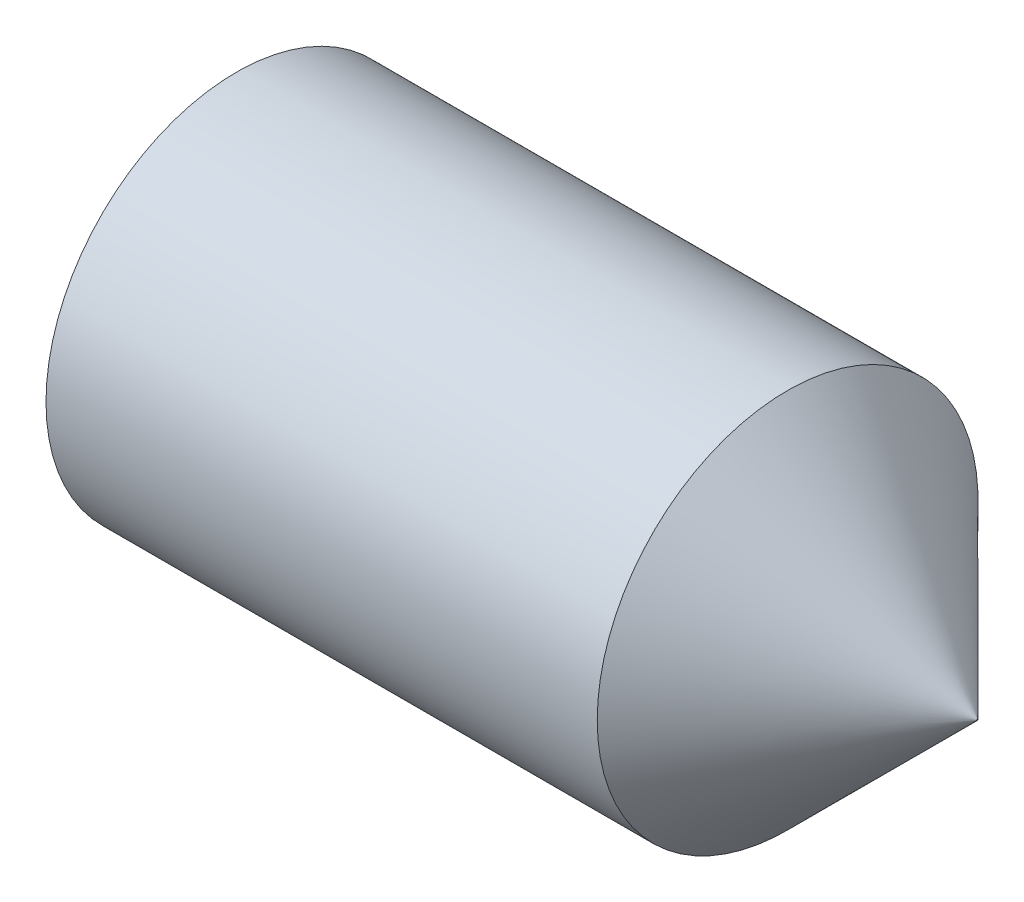
SolidWorks part; units mm, degrees
revolve "BaseBody" add sketch "BodySke" angle 360 about L5
sketch "BodySke" plane through (0, 0, 0) normal (0, 0, 1) x (1, 0, 0)
  line L0 (0, 0) -> (0, 1.2195)
  line L1 (0, 1.2195) -> (0.1619, 1.5)
  line L2 (0.1619, 1.5) -> (4.505, 1.5)
  line L3 (6, 0) -> (6, 0.005)
  line L4 (6, 0) -> (0, 0)
  line L5 (-12.7, 0) -> (88.9, 0) construction
  line L6 (6, 0.005) -> (4.505, 1.5)
  line L7 (0.5, 15.875) -> (0.5, -3.175) construction
  line L8 (0, -1.2195) -> (0.1619, -1.5) construction
  line L9 (6, -0.005) -> (4.505, -1.5) construction
  dimension "Diameter" = 3
  dimension "Drive_ch_ang" = 60
  dimension "Minor_dia" = 2.439
  dimension "Advance" = 0.5
  dimension "Length" = 6
  dimension "Tip_dia" = 0.01
  dimension "Cone_ang" = 90
cosmetic thread "ThreadCosmetic" [suppressed] parameters "Thread_minor"=2.439
ref_plane "Plane1" through (0, 0, 0) normal (0, 0, 1) x (1, 0, 0)
ref_plane "Plane2" through (0, 0, 0) normal (0, 1, 0) x (1, 0, 0)
ref_plane "Plane3" through (0, 0, 0) normal (1, 0, 0) x (0, 0, -1)
sketch "Sketch2" plane through (0, 0, 0) normal (-1, 0, 0) x (0, 0, 1)
  line L0 (0.433, 0.75) -> (-0.433, 0.75)
  line L1 (-0.433, 0.75) -> (-0.866, 0)
  line L2 (0.433, 0.75) -> (0.866, 0)
  line L3 (0.433, -0.75) -> (0.866, 0)
  line L4 (0.433, -0.75) -> (-0.433, -0.75)
  line L5 (-0.433, -0.75) -> (-0.866, 0)
  dimension "Hex_size" = 1.5
  dimension "D2" = 0.75
  dimension "D3" = 0.75
extrude "Hex" cut sketch "Sketch2" against normal blind 2.1
sketch "Sketch4" plane through (0, 4.7709, -0.5249) normal (-1, 0, 0) x (0, 0, 1)
  line L0 (0.5249, -4.7709) -> (1.3124, -4.7709)
  line L1 (0.5249, -4.7709) -> (6.6732, -1.2211) construction
  line L2 (0.5249, -4.7709) -> (0.9186, -4.0889)
  line L3 (1.153, -4.6137) -> (1.2782, -4.5415)
  line L4 (0.975, -4.3054) -> (1.1002, -4.2332)
  arc A0 (1.153, -4.6137) -> (0.975, -4.3054) centre (0.5249, -4.7709) ccw
  arc A1 (1.3124, -4.7709) -> (1.2782, -4.5415) centre (0.5249, -4.7709) ccw
  arc A2 (0.9186, -4.0889) -> (1.1002, -4.2332) centre (0.5249, -4.7709) cw
  circle A3 centre (0.5249, -4.7709) radius 0.6475 construction
  circle A4 centre (0.5249, -4.7709) radius 0.7875 construction
  dimension "Spline_n_dim" = 1.295
  dimension "Spline_m_dim" = 1.575
  dimension "D1" = 30
  dimension "Spline_a_dim" = 60
  dimension "Spline_p_dim" = 0.356
  dimension "D3" = 0.178
extrude "Spline6" [suppressed] cut sketch "Sketch4" against normal blind 1.2
pattern_circular "CirPattern1" [suppressed] count 6 every 60 about axis through (-12.7, 0, 0) along (1, 0, 0)
sketch "Sketch5" plane through (0, 1.4735, 6.925) normal (-1, 0, 0) x (0, 0, 1)
  line L0 (-6.925, -1.4735) -> (-6.1375, -1.4735)
  line L1 (-6.925, -1.4735) -> (-1.9049, 3.5466) construction
  line L2 (-6.925, -1.4735) -> (-6.925, -0.686)
  line L3 (-6.3413, -1.1415) -> (-6.2567, -1.0569)
  line L4 (-6.5931, -0.8898) -> (-6.5085, -0.8052)
  line L5 (-6.5931, -0.8898) -> (-6.3413, -1.1415)
  arc A1 (-6.1375, -1.4735) -> (-6.2567, -1.0569) centre (-6.925, -1.4735) ccw
  arc A2 (-6.925, -0.686) -> (-6.5085, -0.8052) centre (-6.925, -1.4735) cw
  circle A3 centre (-6.925, -1.4735) radius 0.6475 construction
  circle A4 centre (-6.925, -1.4735) radius 0.7875 construction
  dimension "Spline_n_dim" = 1.295
  dimension "Spline_m_dim" = 1.575
  dimension "Spline_p_dim" = 0.356
  dimension "D3" = 0.178
  dimension "D1" = 45
  dimension "Spline_a_dim" = 90
extrude "Spline4" [suppressed] cut sketch "Sketch5" against normal blind 1.2
pattern_circular "CirPattern2" [suppressed] count 4 every 90 about axis through (-12.7, 0, 0) along (1, 0, 0)
sketch "ThdSchSke" plane through (0, 0, 0) normal (0, 0, 1) x (1, 0, 0)
  line L0 (0.1619, -1.2195) -> (-0.0345, -1.5)
  line L1 (0.1619, -1.2195) -> (0.3584, -1.5)
  line L2 (0.3584, -1.5) -> (0.3584, -1.875)
  line L3 (-3.175, 0) -> (5.1513, 0) construction
  line L4 (0.1619, 1.5) -> (0.1619, -1.5) construction
  line L5 (0.3584, -1.875) -> (-0.0345, -1.875)
  line L6 (-0.0345, -1.875) -> (-0.0345, -1.5)
  dimension "Thread_minor" = 2.439
  dimension "Diameter" = 3
revolve "ThreadSchematic" [suppressed] cut sketch "ThdSchSke" angle 360 about L3
pattern_linear "ThdSchPat" [suppressed]
equation "\"D2@Sketch2\" = \"Hex_size@Sketch2\" / 2"
equation "\"D3@Sketch2\" = \"Hex_size@Sketch2\" / 2"
equation "\"Thread_minor@ThreadCosmetic\" = \"Minor_dia@BodySke\""
equation "\"D1@Sketch4\" = \"Spline_a_dim@Sketch4\" / 2"
equation "\"D3@Sketch4\" = \"Spline_p_dim@Sketch4\" / 2"
equation "\"D2@CirPattern1\" = \"Spline_a_dim@Sketch4\""
equation "\"Num_teeth@CirPattern1\" = 360 / \"D2@CirPattern1\""
equation "\"Spline_a_dim@Sketch5\" = 90"
equation "\"Spline_p_dim@Sketch5\" = \"Spline_p_dim@Sketch4\""
equation "\"Spline_m_dim@Sketch5\" = \"Spline_m_dim@Sketch4\""
equation "\"Spline_n_dim@Sketch5\" = \"Spline_n_dim@Sketch4\""
equation "\"D1@Sketch5\" = \"Spline_a_dim@Sketch5\" / 2"
equation "\"D3@Sketch5\" = \"Spline_p_dim@Sketch5\" / 2"
equation "\"Key_eng@Spline4\" = \"Key_eng@Spline6\""
equation "\"Thread_minor@ThdSchSke\" = \"Thread_minor@ThreadCosmetic\""
equation "\"Diameter@ThdSchSke\" = \"Diameter@BodySke\""
equation "\"Overcut@ThdSchSke\" = \"Diameter@BodySke\" * 1.25"
equation "\"Num_threads@ThdSchPat\" = int( (\"Length@BodySke\" - ( ( ( \"Diameter@BodySke\" - \"Minor_dia@BodySke\" ) * 0.5 ) / tan( \"Drive_ch_ang@BodySke\" * 0.017453292 ) ) - ( ( \"Diameter@BodySke\" * 0.5 ) / tan( \"Cone_ang@BodySke\" * 0.008726646 ) ) ) / \"Advance@BodySke\" + 0.999 )  + 1"
equation "\"Num_threads@ThdSchPat\" = int( (\"Length@BodySke\" - ( ( ( \"Diameter@BodySke\" - \"Minor_dia@BodySke\" ) * 0.5 ) / tan( \"Drive_ch_ang@BodySke\" * 0.017453292 ) ) - ( (( \"Diameter@BodySke\" - \"Tip_dia@BodySke\") * 0.5 ) / tan( \"Cone_ang@BodySke\" * 0.008726646 ) ) ) / \"Advance@BodySke\" + 0.999 )  + 1"
equation "\"Advance@ThdSchPat\" = (\"Length@BodySke\" - ( ( ( \"Diameter@BodySke\" - \"Minor_dia@BodySke\" ) * 0.5 ) / tan( \"Drive_ch_ang@BodySke\" * 0.017453292 ) ) - ( ( \"Diameter@BodySke\" * 0.5 ) / tan( \"Cone_ang@BodySke\" * 0.008726646 ) ) ) /  (\"Num_threads@ThdSchPat\" - 1) 'relax it"
equation "\"Advance@ThdSchPat\" = (\"Length@BodySke\" - ( ( ( \"Diameter@BodySke\" - \"Minor_dia@BodySke\" ) * 0.5 ) / tan( \"Drive_ch_ang@BodySke\" * 0.017453292 ) ) - ( ( (\"Diameter@BodySke\" - \"Tip_dia@BodySke\") * 0.5 ) / tan( \"Cone_ang@BodySke\" * 0.008726646 ) ) ) /  (\"Num_threads@ThdSchPat\" - 1) 'relax it"
equation "' \"Num_threads@ThdSchPat\" = \"Num_threads@ThdSchPat\" - sgn( \"Num_threads@ThdSchPat\" - 1) '---chamfered tips only---"
